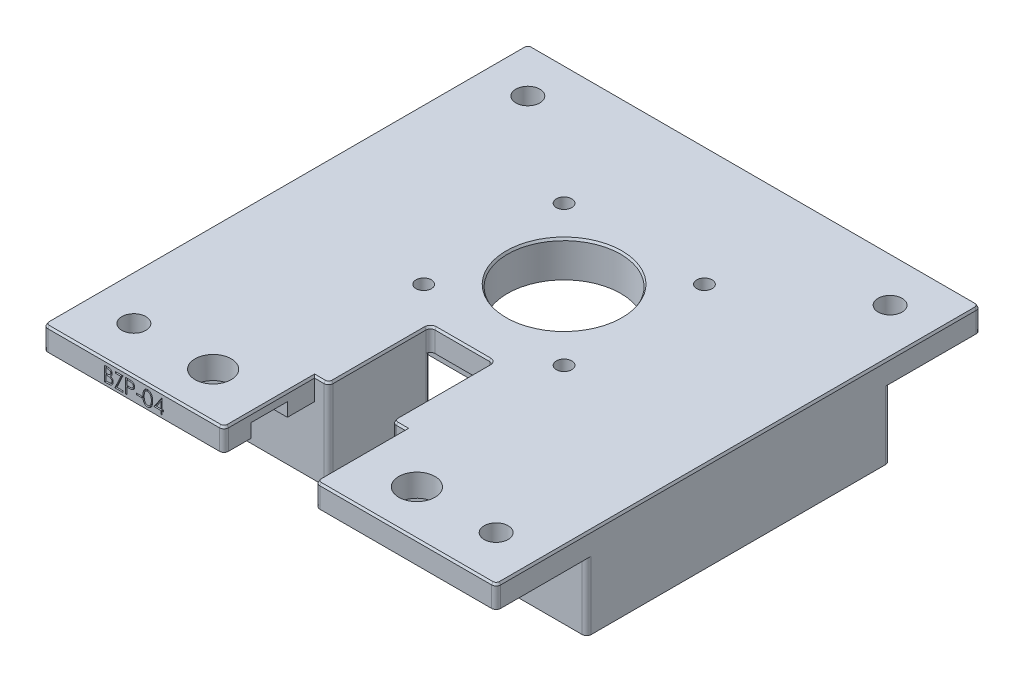
SolidWorks part; units mm, degrees
ref_plane "Front" through (0, 0, 0) normal (0, 0, 1) x (1, 0, 0)
ref_plane "Top" through (0, 0, 0) normal (0, 1, 0) x (1, 0, 0)
ref_plane "Right" through (0, 0, 0) normal (1, 0, 0) x (0, 0, -1)
sketch "Sketch2" plane through (0, 0, 0) normal (0, 1, 0) x (1, 0, 0)
  line L1 (0, 0) -> (100, 0)
  line L2 (0, 0) -> (0, 107)
  line L3 (0, 107) -> (100, 107)
  line L4 (100, 0) -> (100, 107)
  dimension "D1" = 107
  dimension "D2" = 100
extrude "Boss-Extrude1" add sketch "Sketch2" along normal blind 5
sketch "Sketch3" plane through (0, 5, 0) normal (0, 1, 0) x (1, 0, 0)
  line L0 (39.9, 0) -> (39.9, 20)
  line L1 (0, 0) -> (100, 0) construction
  line L2 (39.9, 20) -> (43, 20)
  line L3 (43, 20) -> (43, 42.5)
  line L4 (43, 42.5) -> (57, 42.5)
  line L5 (57, 42.5) -> (57, 20)
  line L6 (57, 20) -> (60.1, 20)
  line L7 (60.1, 20) -> (60.1, 0)
  line L8 (60.1, 0) -> (39.9, 0)
  line L9 (50, 107) -> (50, 65) construction
  line L10 (100, 107) -> (0, 107) construction
  line L11 (43, 42.5) -> (27.5, 42.5) construction
  line L12 (27.5, 87.5) -> (72.5, 87.5) construction
  line L13 (27.5, 87.5) -> (27.5, 42.5) construction
  line L14 (34.5, 49.5) -> (65.5, 49.5) construction
  line L15 (34.5, 49.5) -> (34.5, 80.5) construction
  line L16 (34.5, 80.5) -> (65.5, 80.5) construction
  line L17 (65.5, 49.5) -> (65.5, 80.5) construction
  line L18 (34.5, 49.5) -> (65.5, 80.5) construction
  line L19 (34.5, 80.5) -> (65.5, 49.5) construction
  line L20 (27.5, 42.5) -> (72.5, 42.5) construction
  line L21 (72.5, 87.5) -> (72.5, 42.5) construction
  line L22 (27.5, 87.5) -> (72.5, 42.5) construction
  line L23 (27.5, 42.5) -> (72.5, 87.5) construction
  line L24 (57, 42.5) -> (72.5, 42.5) construction
  line L25 (40, 10) -> (27.5, 10) construction
  line L26 (75, 47) -> (25, 47) construction
  line L27 (75, 47) -> (75, 83) construction
  line L28 (75, 83) -> (25, 83) construction
  line L29 (25, 47) -> (25, 83) construction
  line L30 (75, 47) -> (25, 83) construction
  line L31 (75, 83) -> (25, 47) construction
  line L32 (50, 65) -> (50, 10) construction
  line L33 (40, 0) -> (60, 0) construction
  line L34 (40, 0) -> (40, 20) construction
  line L35 (40, 20) -> (60, 20) construction
  line L36 (60, 0) -> (60, 20) construction
  line L37 (40, 0) -> (60, 20) construction
  line L38 (40, 20) -> (60, 0) construction
  circle A0 centre (50, 65) radius 12.5
  circle A1 centre (65.5, 49.5) radius 1.7
  circle A2 centre (34.5, 49.5) radius 1.7
  circle A3 centre (65.5, 80.5) radius 1.7
  circle A4 centre (34.5, 80.5) radius 1.7
  circle A5 centre (25, 83) radius 1.7 construction
  circle A6 centre (25, 47) radius 1.7 construction
  circle A7 centre (75, 47) radius 1.7 construction
  circle A8 centre (75, 83) radius 1.7 construction
  circle A9 centre (27.5, 10) radius 4
  circle A10 centre (72.5, 10) radius 4
  point P11 (50, 0)
  point P12 (50, 0)
  point P42 (50, 10)
  dimension "D4" = 25
  dimension "D6" = 3.4
  dimension "D10" = 3.4
  dimension "D12" = 8
  dimension "D2" = 14
  dimension "D3" = 20.2
  dimension "D5" = 31
  dimension "D7" = 42
  dimension "D8" = 50
  dimension "D9" = 36
  dimension "D11" = 45
  dimension "D13" = 20
  dimension "D14" = 12.5
  dimension "D15" = 20
extrude "Cut-Extrude1" cut sketch "Sketch3" against normal through all both and the other way through all
hole_wizard "M5 Clearance Hole1" positions "Sketch6" profile "Sketch5" hole size "M5" standard "ANSI Metric" end condition through all
sketch "Sketch6" plane through (0, 5, 0) normal (0, 1, 0) x (1, 0, 0)
  line L0 (0, 97) -> (100, 97) construction
  line L1 (0, 107) -> (0, 0) construction
  line L2 (100, 0) -> (100, 107) construction
  line L5 (10, 107) -> (10, 0) construction
  line L6 (100, 107) -> (0, 107) construction
  line L7 (0, 0) -> (39.9, 0) construction
  line L10 (90, 107) -> (90, 0) construction
  line L11 (60.1, 0) -> (100, 0) construction
  line L14 (0, 10) -> (100, 10) construction
  point P0 (10, 97)
  point P2 (10, 10)
  point P4 (90, 10)
  point P6 (90, 97)
  dimension "D1" = 10
  dimension "D2" = 10
  dimension "D3" = 10
  dimension "D4" = 10
sketch "Sketch5" plane through (10, 5, -97) normal (1, 0, 0) x (0, 0, 1)
  line L0 (0, 0) -> (0, 5)
  line L1 (0, 5) -> (2.65, 5)
  line L2 (2.65, 5) -> (2.65, 0)
  line L5 (2.65, 0) -> (0, 0)
  line L11 (0, -6.35) -> (0, 107.95) construction
  dimension "Thru Hole Dia." = 5.3
  dimension "Thru Hole Depth" = 5
fillet "Fillet1" radius 1 8 edges at (60.1, 2.5, 0) (39.9, 2.5, 0) (0, 2.5, -107) (100, 2.5, -107) (100, 2.5, 0) (0, 2.5, 0) (57, 2.5, -42.5) (43, 2.5, -42.5)
sketch "Sketch7" plane through (0, 0, 0) normal (0, -1, 0) x (1, 0, 0)
  line L0 (57, -20) -> (100, -20)
  line L1 (100, -1) -> (100, -106) construction
  line L2 (100, -20) -> (100, -87)
  line L3 (100, -87) -> (84, -87)
  line L4 (84, -87) -> (84, -82)
  line L5 (84, -82) -> (95, -82)
  line L6 (95, -82) -> (95, -25)
  line L7 (95, -25) -> (57, -25) construction
  line L8 (57, -25) -> (57, -20)
  line L9 (61.1, 0) -> (99, 0) construction
  line L10 (57, -20) -> (57, -41.5) construction
  line L11 (99, -107) -> (1, -107) construction
  line L12 (50, -107) -> (50, -46.1063) construction
  line L13 (43, -25) -> (43, -20)
  line L14 (5, -25) -> (43, -25) construction
  line L15 (5, -82) -> (5, -25)
  line L16 (16, -82) -> (5, -82)
  line L17 (16, -87) -> (16, -82)
  line L18 (0, -87) -> (16, -87)
  line L19 (0, -20) -> (0, -87)
  line L20 (43, -20) -> (0, -20)
  line L21 (57, -25) -> (57, -42.5)
  line L23 (57, -42.5) -> (62, -42.5)
  line L25 (62, -42.5) -> (62, -25)
  line L26 (62, -25) -> (95, -25)
  line L27 (38, -25) -> (5, -25)
  line L28 (38, -42.5) -> (38, -25)
  line L29 (43, -25) -> (43, -42.5)
  line L31 (43, -42.5) -> (38, -42.5)
  line L32 (56, -42.5) -> (44, -42.5) construction
  dimension "D1" = 20
  dimension "D2" = 20
  dimension "D3" = 16
  dimension "D4" = 5
  dimension "D5" = 5
extrude "Boss-Extrude2" add sketch "Sketch7" along normal blind 15
fillet "Fillet3" radius 3 6 edges at (5, -7.5, -82) (95, -7.5, -82) (5, -7.5, -25) (38, -7.5, -25) (95, -7.5, -25) (62, -7.5, -25)
fillet "Fillet4" radius 1 14 edges at (100, -7.5, -87) (100, -7.5, -20) (43, -5, -20) (57, -5, -20) (84, -7.5, -87) (84, -7.5, -82) (0, -7.5, -20) (0, -7.5, -87) (16, -7.5, -87) (16, -7.5, -82) (38, -7.5, -42.5) (62, -7.5, -42.5) (57, -7.5, -42.5) (43, -7.5, -42.5)
ref_plane "Plane1" through (0, 0, -10) normal (0, 0, 1) x (1, 0, 0)
sketch "Sketch9" plane through (0, 0, -10) normal (0, 0, 1) x (1, 0, 0)
  line L0 (39.9, 0) -> (39.9, 3)
  line L2 (39.9, 0) -> (39.9, 5) construction
  line L3 (39.9, 3) -> (36.9, 0)
  line L4 (36.9, 0) -> (39.9, 0)
  line L5 (60.1, 0) -> (63.1, 0)
  line L6 (99, 0) -> (60.1, 0) construction
  line L7 (63.1, 0) -> (60.1, 3)
  line L8 (60.1, 0) -> (60.1, 5) construction
  line L9 (60.1, 3) -> (60.1, 0)
  dimension "D1" = 45
  dimension "D2" = 3
extrude "Cut-Extrude2" cut sketch "Sketch9" against normal blind 4 and the other way blind 4
sketch "Sketch12" plane through (0, 0, 0) normal (0, -1, 0) x (1, 0, 0)
  line L0 (34.5, -85.5) -> (65.5, -85.5)
  line L1 (70.5, -80.5) -> (70.5, -49.5)
  line L2 (65.5, -44.5) -> (34.5, -44.5)
  line L3 (29.5, -49.5) -> (29.5, -80.5)
  circle A0 centre (34.5, -80.5) radius 5 construction
  circle A1 centre (65.5, -80.5) radius 5 construction
  circle A2 centre (65.5, -49.5) radius 5 construction
  circle A3 centre (34.5, -49.5) radius 5 construction
  arc A4 (65.5, -85.5) -> (70.5, -80.5) centre (65.5, -80.5) ccw
  arc A5 (34.5, -85.5) -> (29.5, -80.5) centre (34.5, -80.5) cw
  arc A6 (65.5, -44.5) -> (70.5, -49.5) centre (65.5, -49.5) cw
  arc A7 (29.5, -49.5) -> (34.5, -44.5) centre (34.5, -49.5) cw
  circle A8 centre (50, -65) radius 12.5 construction
  circle A9 centre (50, -65) radius 12.5
  circle A10 centre (34.5, -49.5) radius 1.7 construction
  circle A11 centre (65.5, -49.5) radius 1.7 construction
  circle A12 centre (65.5, -80.5) radius 1.7 construction
  circle A13 centre (34.5, -80.5) radius 1.7 construction
  circle A14 centre (34.5, -49.5) radius 1.7
  circle A15 centre (65.5, -49.5) radius 1.7
  circle A16 centre (65.5, -80.5) radius 1.7
  circle A17 centre (34.5, -80.5) radius 1.7
  dimension "D1" = 10
extrude "Boss-Extrude3" add sketch "Sketch12" along normal blind 3
chamfer "Chamfer2" distance 0.5 angle 45 8 edges at (50, 0, -85.5) (69.0355, 0, -84.0355) (30.9645, 0, -84.0355) (70.5, 0, -65) (29.5, 0, -65) (69.0355, 0, -45.9645) (30.9645, 0, -45.9645) (50, 0, -44.5)
sketch "Sketch10" plane through (0, 5, 0) normal (0, 0, -1) x (1, 0, 0)
  line L0 (0, 4.4) -> (39.9, 4.4) construction
  line L2 (1, 5) -> (38.9, 5) construction
  line L5 (39.9, 0) -> (39.9, 5) construction
  text T0 "BZP-04" font "Century Gothic" height in points 12
  dimension "D1" = 0.6
extrude "Part Num" cut sketch "Sketch10" along normal blind 0.4
chamfer "Printability Chamfer" distance 0.5 angle 30 23 edges at (59.05, 5, -20) (57.2929, 5, -20.2929) (57, 5, -31.25) (56.7071, 5, -42.2071) (50, 5, -42.5) (43.2929, 5, -42.2071) (43, 5, -31.25) (42.7071, 5, -20.2929) (40.95, 5, -20) (50, 5, -77.5) (60.1, 5, -10.5) (60.3929, 5, -0.2929) (80.05, 5, 0) (99.7071, 5, -0.2929) (100, 5, -53.5) (99.7071, 5, -106.7071) (50, 5, -107) (0.2929, 5, -106.7071) (0, 5, -53.5) (39.9, 5, -10.5) (0.2929, 5, -0.2929) (39.6071, 5, -0.2929) (19.95, 5, 0)
equation "\"D5@Sketch7\"=\"D4@Sketch7\""
